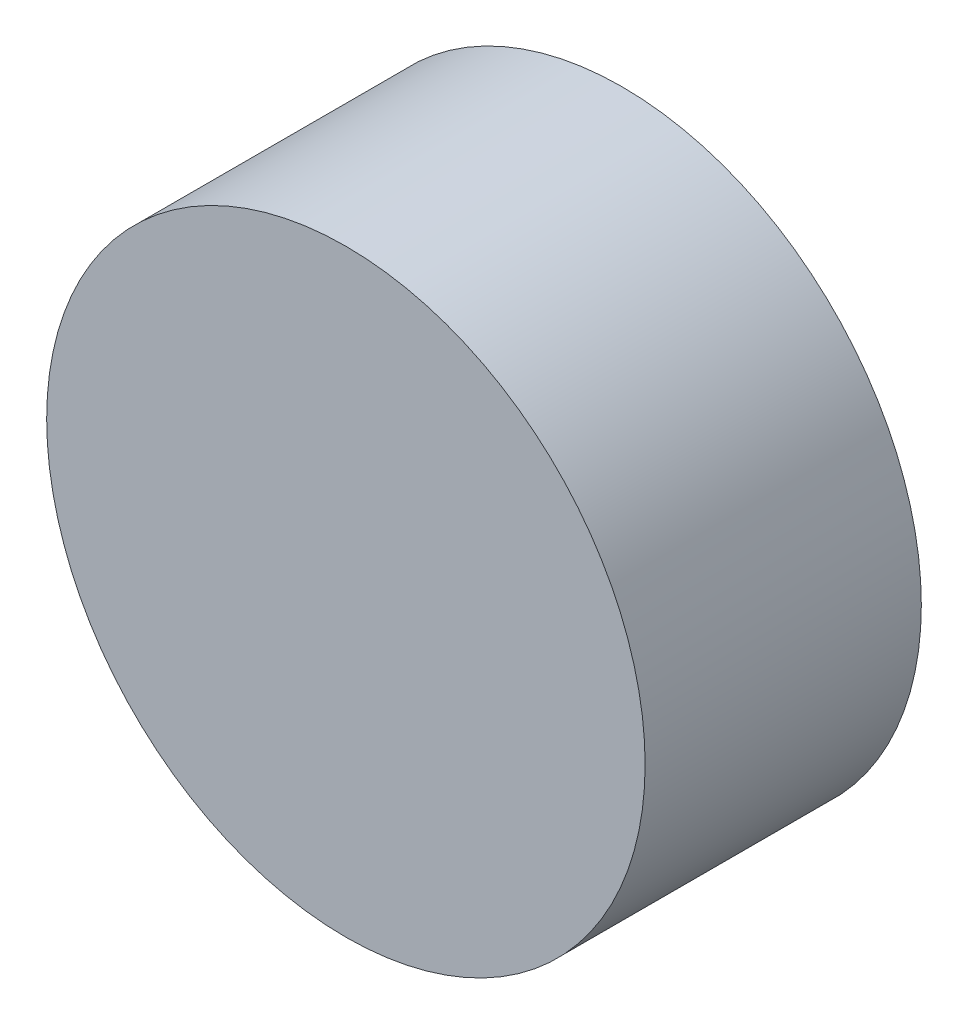
SolidWorks part; units mm, degrees
ref_plane "前视基准面" through (0, 0, 0) normal (0, 0, 1) x (1, 0, 0)
ref_plane "上视基准面" through (0, 0, 0) normal (0, 1, 0) x (1, 0, 0)
ref_plane "右视基准面" through (0, 0, 0) normal (1, 0, 0) x (0, 0, -1)
sketch "草图1" plane through (0, 0, 0) normal (0, 0, 1) x (1, 0, 0)
  circle A0 centre (0, 0) radius 3.25
  dimension "D1" = 6.5
extrude "凸台-拉伸1" add sketch "草图1" along normal blind 3
